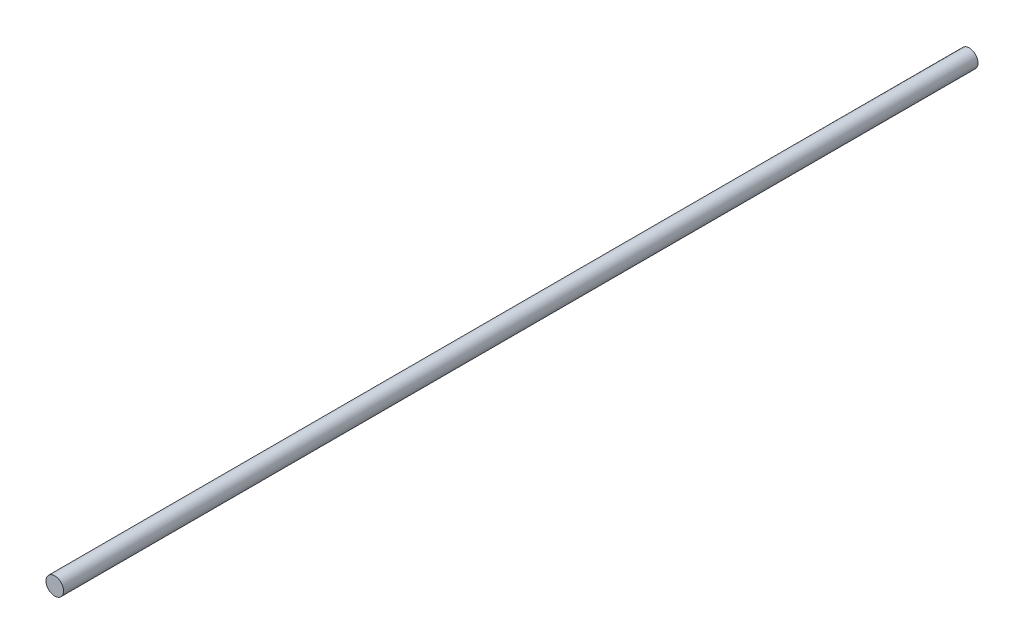
SolidWorks part; units mm, degrees
ref_plane "Front Plane" through (0, 0, 0) normal (0, 0, 1) x (1, 0, 0)
ref_plane "Top Plane" through (0, 0, 0) normal (0, 1, 0) x (1, 0, 0)
ref_plane "Right Plane" through (0, 0, 0) normal (1, 0, 0) x (0, 0, -1)
sketch "Sketch1" plane through (0, 0, 0) normal (0, 0, 1) x (1, 0, 0)
  circle A0 centre (0, 0) radius 3.175
  dimension "D1" = 6.35
extrude "Boss-Extrude1" add sketch "Sketch1" along normal blind 330.2
